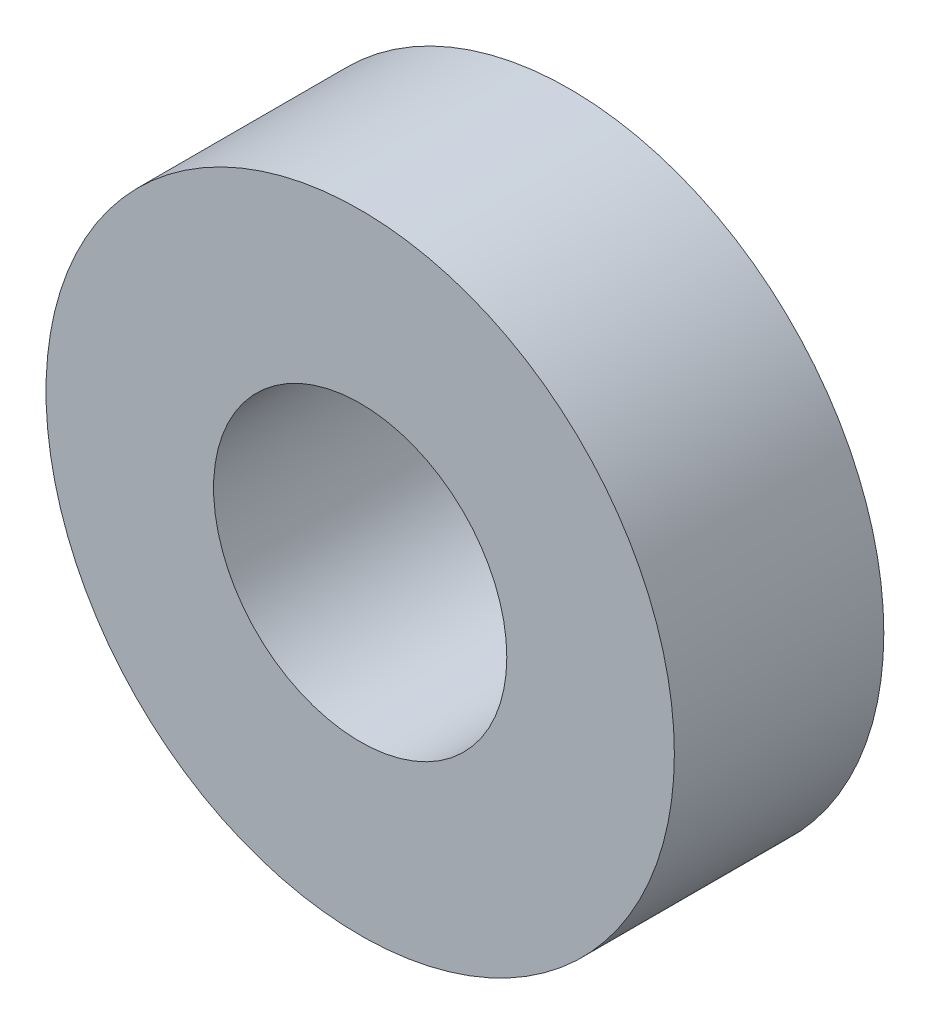
SolidWorks part; units mm, degrees
material "Stainless Steel (ferritic)"
ref_plane "Front Plane" through (0, 0, 0) normal (0, 0, 1) x (1, 0, 0)
ref_plane "Top Plane" through (0, 0, 0) normal (0, 1, 0) x (1, 0, 0)
ref_plane "Right Plane" through (0, 0, 0) normal (1, 0, 0) x (0, 0, -1)
sketch "Sketch1" plane through (0, 0, 0) normal (0, 0, 1) x (1, 0, 0)
  circle A0 centre (0, 0) radius 7
  circle A1 centre (0, 0) radius 15
extrude "Boss-Extrude1" add sketch "Sketch1" along normal blind 10
scale "Scale1" scale about centroid uniform scaling yes scale factor 2.3
